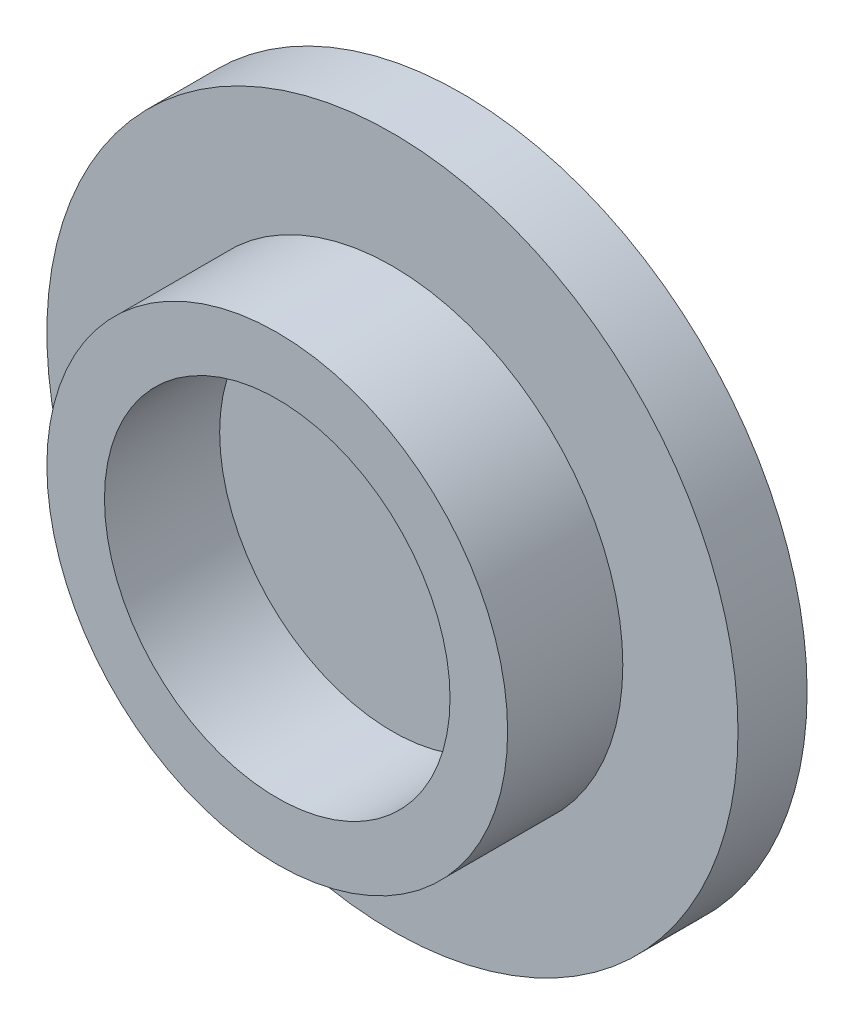
SolidWorks part; units mm, degrees
ref_plane "Front Plane" through (0, 0, 0) normal (0, 0, 1) x (1, 0, 0)
ref_plane "Top Plane" through (0, 0, 0) normal (0, 1, 0) x (1, 0, 0)
ref_plane "Right Plane" through (0, 0, 0) normal (1, 0, 0) x (0, 0, -1)
sketch "Sketch1" plane through (0, 0, 0) normal (0, 0, 1) x (1, 0, 0)
  circle A0 centre (0, 0) radius 15
  dimension "D1" = 30
extrude "Boss-Extrude1" add sketch "Sketch1" along normal blind 3
ref_plane "Plane1" through (0, 0, 3) normal (0, 0, 1) x (1, 0, 0)
sketch "Sketch2" plane through (0, 0, 3) normal (0, 0, 1) x (1, 0, 0)
  circle A0 centre (0, 0) radius 10
  circle A1 centre (0, 0) radius 7.5
  dimension "D1" = 20
  dimension "D2" = 15
extrude "Boss-Extrude2" add sketch "Sketch2" along normal blind 5
